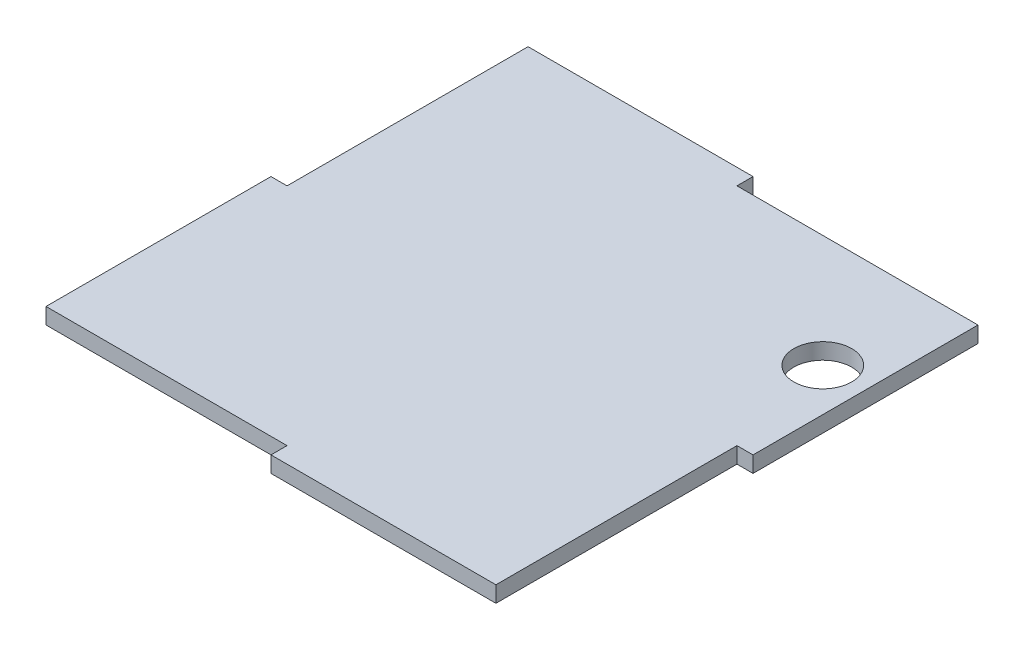
SolidWorks part; units mm, degrees
material "Acrylic (Medium-high impact)"
ref_plane "Front Plane" through (0, 0, 0) normal (0, 0, 1) x (1, 0, 0)
ref_plane "Top Plane" through (0, 0, 0) normal (0, 1, 0) x (1, 0, 0)
ref_plane "Right Plane" through (0, 0, 0) normal (1, 0, 0) x (0, 0, -1)
sketch "Sketch1" plane through (0, 0, 0) normal (0, 1, 0) x (1, 0, 0)
  line L0 (-112.5062, 93.4401) -> (-112.5062, 99.7901)
  line L1 (-112.5062, 93.4401) -> (65.2938, 93.4401)
  line L2 (-112.5062, 93.4401) -> (-112.5062, -84.3599)
  line L3 (-112.5062, -84.3599) -> (65.2938, -84.3599)
  line L4 (65.2938, 93.4401) -> (65.2938, -84.3599)
  line L5 (-112.5062, 99.7901) -> (-23.6062, 99.7901)
  line L6 (-23.6062, 99.7901) -> (-23.6062, 93.4401)
  line L7 (-112.5062, -84.3599) -> (-118.8562, -84.3599)
  line L8 (-118.8562, -84.3599) -> (-118.8562, 4.5401)
  line L9 (-118.8562, 4.5401) -> (-112.5062, 4.5401)
  line L10 (65.2938, -84.3599) -> (65.2938, -90.7099)
  line L11 (65.2938, -90.7099) -> (-23.6062, -90.7099)
  line L12 (-23.6062, -90.7099) -> (-23.6062, -84.3599)
  line L13 (65.2938, 93.4401) -> (71.6438, 93.4401)
  line L14 (71.6438, 93.4401) -> (71.6438, 4.5401)
  line L15 (71.6438, 4.5401) -> (65.2938, 4.5401)
  circle A0 centre (54.7528, 48.9901) radius 11.43
  point P4 (-23.6062, 93.4401)
  point P5 (-112.5062, 4.5401)
  point P9 (65.2938, 4.5401)
  point P10 (-23.6062, -84.3599)
  point P20 (54.7528, 48.9901)
  dimension "D8" = 22.86
  dimension "D1" = 177.8
  dimension "D2" = 177.8
  dimension "D3" = 6.35
  dimension "D4" = 6.35
  dimension "D5" = 6.35
  dimension "D6" = 6.35
  dimension "D7" = 44.45
  dimension "D9" = 10.541
extrude "Boss-Extrude1" add sketch "Sketch1" along normal blind 6.35 contours L9 L8 L7 L2 | L6 L5 L0 L1 | L4 L1 L2 L3 | L15 L14 L13 L4 | L12 L11 L10 L3
